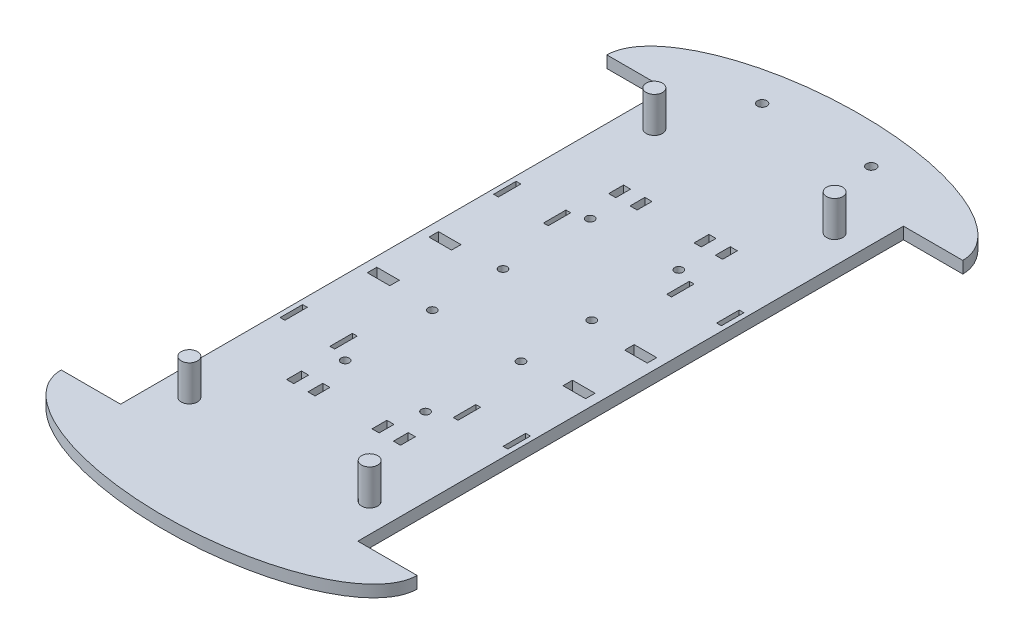
SolidWorks part; units mm, degrees
ref_plane "Front Plane" through (0, 0, 0) normal (0, 0, 1) x (1, 0, 0)
ref_plane "Top Plane" through (0, 0, 0) normal (0, 1, 0) x (1, 0, 0)
ref_plane "Right Plane" through (0, 0, 0) normal (1, 0, 0) x (0, 0, -1)
sketch "Sketch6" plane through (0, 0, 0) normal (0, 1, 0) x (1, 0, 0)
  line L0 (-75, -115) -> (75, -115)
  line L1 (-50, 115) -> (50, 115)
  line L2 (-50, 115) -> (-50, -115)
  line L3 (-50, -115) -> (50, -115)
  line L4 (50, 115) -> (50, -115)
  line L5 (-50, 115) -> (50, -115) construction
  line L6 (-50, -115) -> (50, 115) construction
  line L7 (-109.8149, 0) -> (148.3409, 0) construction
  line L8 (-75, 115) -> (75, 115)
  ellipse E0 centre (0, -115) end of major axis (75, -115) minor radius 31.707
  ellipse E1 centre (0, 115) end of major axis (75, 115) minor radius 31.707
  point P0 (0, 0)
  point P9 (0, -115)
  dimension "D1" = 230
  dimension "D2" = 100
extrude "Boss-Extrude10" add sketch "Sketch6" along normal blind 5 contours E1 L8 L1 | E1 L4 L1 L2 | L4 E1 L2 E0 | L4 E0 L2 L0 | L0 E0
sketch "Sketch8" plane through (0, 0, 0) normal (0, -1, 0) x (1, 0, 0)
sketch "Sketch9" plane through (0, 5, 0) normal (0, 1, 0) x (1, 0, 0)
  line L0 (-25, -45) -> (-25, -49.75) construction
  line L1 (-55, 0) -> (55, 0) construction
  line L2 (-46, -49.75) -> (-46, -40.25) construction
  line L3 (-48, -49.75) -> (-46, -49.75) construction
  line L4 (-48, -45) -> (-48, -40.25) construction
  line L5 (-48, 45) -> (-48, 49.75) construction
  line L6 (-48, 45) -> (-48, 40.25) construction
  line L7 (-48, 49.75) -> (-46, 49.75) construction
  line L8 (-46, 49.75) -> (-46, 40.25) construction
  line L9 (-48, -45) -> (-48, -49.75) construction
  line L10 (-48, 49.75) -> (-46, 49.75)
  line L11 (-48, 49.75) -> (-48, 40.25)
  line L12 (-48, 40.25) -> (-46, 40.25)
  line L13 (-46, 49.75) -> (-46, 40.25)
  line L14 (-46, -49.75) -> (-46, -40.25)
  line L15 (-48, -40.25) -> (-46, -40.25)
  line L16 (-48, -49.75) -> (-48, -40.25)
  line L17 (-48, -49.75) -> (-46, -49.75)
  line L18 (0, -55) -> (0, 55) construction
  line L19 (46, 49.75) -> (46, 40.25) construction
  line L20 (48, 49.75) -> (46, 49.75) construction
  line L21 (48, 45) -> (48, 40.25) construction
  line L22 (48, 45) -> (48, 49.75) construction
  line L23 (46, 49.75) -> (46, 40.25)
  line L24 (48, 40.25) -> (46, 40.25)
  line L25 (48, 49.75) -> (48, 40.25)
  line L26 (48, 49.75) -> (46, 49.75)
  line L27 (48, -45) -> (48, -49.75) construction
  line L28 (48, -45) -> (48, -40.25) construction
  line L29 (48, -49.75) -> (46, -49.75) construction
  line L30 (46, -49.75) -> (46, -40.25) construction
  line L31 (48, -49.75) -> (46, -49.75)
  line L32 (48, -49.75) -> (48, -40.25)
  line L33 (48, -40.25) -> (46, -40.25)
  line L34 (46, -49.75) -> (46, -40.25)
  line L35 (-27, 49.75) -> (-27, 40.25) construction
  line L37 (-25, 49.75) -> (-27, 49.75) construction
  line L38 (-25, 45) -> (-25, 40.25) construction
  line L39 (-25, 45) -> (-25, 49.75) construction
  line L40 (-27, 49.75) -> (-27, 40.25)
  line L41 (-25, 40.25) -> (-27, 40.25)
  line L42 (-25, 49.75) -> (-25, 40.25)
  line L43 (-25, 49.75) -> (-27, 49.75)
  line L44 (-25, -45) -> (-25, -40.25) construction
  line L45 (-25, -49.75) -> (-27, -49.75) construction
  line L46 (-27, -49.75) -> (-27, -40.25) construction
  line L47 (-25, -49.75) -> (-27, -49.75)
  line L48 (-25, -49.75) -> (-25, -40.25)
  line L49 (-25, -40.25) -> (-27, -40.25)
  line L50 (-27, -49.75) -> (-27, -40.25)
  line L51 (27, -49.75) -> (27, -40.25) construction
  line L52 (25, -49.75) -> (27, -49.75) construction
  line L53 (25, -45) -> (25, -40.25) construction
  line L54 (25, -45) -> (25, -49.75) construction
  line L55 (27, -49.75) -> (27, -40.25)
  line L56 (25, -40.25) -> (27, -40.25)
  line L57 (25, -49.75) -> (25, -40.25)
  line L58 (25, -49.75) -> (27, -49.75)
  line L59 (25, 45) -> (25, 49.75) construction
  line L60 (25, 45) -> (25, 40.25) construction
  line L61 (25, 49.75) -> (27, 49.75) construction
  line L62 (27, 49.75) -> (27, 40.25) construction
  line L63 (25, 49.75) -> (27, 49.75)
  line L64 (25, 49.75) -> (25, 40.25)
  line L65 (25, 40.25) -> (27, 40.25)
  line L66 (27, 49.75) -> (27, 40.25)
extrude "Cut-Extrude2" cut sketch "Sketch9" against normal through all
sketch "Sketch10" plane through (0, 5, 0) normal (0, 1, 0) x (1, 0, 0)
  line L0 (-15, -64.75) -> (-12, -64.75) construction
  line L2 (-15, -71) -> (-15, -64.75) construction
  line L3 (-24, -71) -> (-21, -71) construction
  line L4 (-24, -71) -> (-24, -64.75) construction
  line L5 (-21, -71) -> (-21, -64.75) construction
  line L6 (-21, -64.75) -> (-24, -64.75) construction
  line L7 (-12, -71) -> (-12, -64.75) construction
  line L8 (-24, -71) -> (-21, -71)
  line L9 (-24, -71) -> (-24, -64.75)
  line L10 (-24, -64.75) -> (-21, -64.75)
  line L11 (-21, -71) -> (-21, -64.75)
  line L12 (0, -55) -> (0, 55) construction
  line L13 (-12, -71) -> (-15, -71) construction
  line L14 (-15, -71) -> (-15, -64.75)
  line L15 (-12, -64.75) -> (-15, -64.75)
  line L16 (-12, -71) -> (-12, -64.75)
  line L17 (-12, -71) -> (-15, -71)
  line L18 (12, -71) -> (15, -71) construction
  line L19 (12, -71) -> (12, -64.75) construction
  line L20 (21, -64.75) -> (24, -64.75) construction
  line L21 (21, -71) -> (21, -64.75) construction
  line L22 (24, -71) -> (24, -64.75) construction
  line L23 (24, -71) -> (21, -71) construction
  line L24 (15, -71) -> (15, -64.75) construction
  line L25 (15, -64.75) -> (12, -64.75) construction
  line L26 (12, -71) -> (15, -71)
  line L27 (12, -71) -> (12, -64.75)
  line L28 (12, -64.75) -> (15, -64.75)
  line L29 (15, -71) -> (15, -64.75)
  line L30 (21, -71) -> (21, -64.75)
  line L31 (24, -64.75) -> (21, -64.75)
  line L32 (24, -71) -> (24, -64.75)
  line L33 (24, -71) -> (21, -71)
  line L34 (-55, 0) -> (55, 0) construction
  line L35 (15, 64.75) -> (12, 64.75) construction
  line L36 (15, 71) -> (15, 64.75) construction
  line L37 (24, 71) -> (21, 71) construction
  line L38 (24, 71) -> (24, 64.75) construction
  line L39 (21, 71) -> (21, 64.75) construction
  line L40 (21, 64.75) -> (24, 64.75) construction
  line L41 (12, 71) -> (12, 64.75) construction
  line L42 (12, 71) -> (15, 71) construction
  line L43 (-12, 71) -> (-15, 71) construction
  line L44 (-12, 71) -> (-12, 64.75) construction
  line L45 (-21, 64.75) -> (-24, 64.75) construction
  line L46 (-21, 71) -> (-21, 64.75) construction
  line L47 (-24, 71) -> (-24, 64.75) construction
  line L48 (-24, 71) -> (-21, 71) construction
  line L49 (-15, 71) -> (-15, 64.75) construction
  line L50 (-15, 64.75) -> (-12, 64.75) construction
  line L51 (24, 71) -> (21, 71)
  line L52 (24, 71) -> (24, 64.75)
  line L53 (24, 64.75) -> (21, 64.75)
  line L54 (21, 71) -> (21, 64.75)
  line L55 (15, 71) -> (15, 64.75)
  line L56 (12, 64.75) -> (15, 64.75)
  line L57 (12, 71) -> (12, 64.75)
  line L58 (12, 71) -> (15, 71)
  line L59 (-12, 71) -> (-15, 71)
  line L60 (-12, 71) -> (-12, 64.75)
  line L61 (-12, 64.75) -> (-15, 64.75)
  line L62 (-15, 71) -> (-15, 64.75)
  line L63 (-21, 71) -> (-21, 64.75)
  line L64 (-24, 64.75) -> (-21, 64.75)
  line L65 (-24, 71) -> (-24, 64.75)
  line L66 (-24, 71) -> (-21, 71)
extrude "Cut-Extrude3" cut sketch "Sketch10" against normal through all
sketch "Sketch11" plane through (0, 5, 0) normal (0, 1, 0) x (1, 0, 0)
  line L0 (0, -55) -> (0, 55) construction
  line L3 (36.5, -15) -> (36.5, -11) construction
  line L4 (36.5, -15) -> (46, -15) construction
  line L5 (-36.5, -15) -> (-46, -15) construction
  line L6 (-36.5, -15) -> (-36.5, -11) construction
  line L7 (46, -15) -> (46, -11)
  line L8 (-36.5, -15) -> (-46, -15)
  line L9 (-36.5, -15) -> (-36.5, -11)
  line L10 (-36.5, -11) -> (-46, -11)
  line L11 (-46, -15) -> (-46, -11)
  line L12 (36.5, -11) -> (46, -11)
  line L13 (36.5, -15) -> (36.5, -11)
  line L14 (36.5, -15) -> (46, -15)
  line L15 (-55, 0) -> (55, 0) construction
  line L16 (-36.5, 15) -> (-36.5, 11) construction
  line L17 (-36.5, 15) -> (-46, 15) construction
  line L18 (36.5, 15) -> (46, 15) construction
  line L19 (36.5, 15) -> (36.5, 11) construction
  line L20 (36.5, 15) -> (46, 15)
  line L21 (36.5, 15) -> (36.5, 11)
  line L22 (36.5, 11) -> (46, 11)
  line L23 (-46, 15) -> (-46, 11)
  line L24 (-36.5, 11) -> (-46, 11)
  line L25 (-36.5, 15) -> (-36.5, 11)
  line L26 (-36.5, 15) -> (-46, 15)
  line L27 (46, 15) -> (46, 11)
extrude "Cut-Extrude4" cut sketch "Sketch11" against normal through all
sketch "Sketch12" plane through (0, 5, 0) normal (0, 1, 0) x (1, 0, 0)
  line L0 (0, 83.293) -> (0, 116.707) construction
  line L1 (0, -55) -> (0, 55) construction
  line L2 (0, 116.707) -> (26.49, 116.707) construction
  line L3 (0, 116.707) -> (-26.49, 116.707) construction
  ellipse E0 centre (0, 115) end of major axis (75, 115) minor radius 31.707 (75, 115) -> (-75, 115) ccw construction
sketch "Sketch13" plane through (0, 5, 0) normal (0, 1, 0) x (1, 0, 0)
  line L0 (-50, 115) -> (50, 115) construction
  line L1 (0, -2.75) -> (0, 2.75) construction
  line L2 (-2.75, 0) -> (2.75, 0) construction
  line L4 (-38, 98) -> (-38, 115) construction
  circle A0 centre (-38, 98) radius 3.415
  circle A1 centre (38, 98) radius 3.415
  circle A2 centre (38, -98) radius 3.415
  circle A3 centre (-38, -98) radius 3.415
extrude "Boss-Extrude11" add sketch "Sketch13" along normal blind 15
sketch "Sketch14" plane through (0, 5, 0) normal (0, 1, 0) x (1, 0, 0)
  line L0 (-36.5, 15) -> (-36.5, 15.06) construction
  line L14 (16.99, -14.95) -> (18.74, -14.95) construction
  circle A0 centre (-18.7434, 14.9502) radius 1.75
  circle A1 centre (-18.7434, 51.6902) radius 1.75
  circle A3 centre (18.6366, 51.6902) radius 1.75
  circle A4 centre (18.6366, 14.9502) radius 1.75
  circle A11 centre (-18.64, -51.69) radius 1.75
  circle A12 centre (-18.64, -14.95) radius 1.75
  circle A13 centre (18.74, -14.95) radius 1.75
  circle A14 centre (16.99, -53.44) radius 1.75
extrude "Cut-Extrude5" cut sketch "Sketch14" against normal through all
sketch "Sketch15" plane through (0, 5, 0) normal (0, 1, 0) x (1, 0, 0)
  line L0 (-50, 115) -> (50, 115) construction
  line L1 (-24.5632, 130) -> (-24.5632, 115) construction
  line L2 (21.4168, 130) -> (21.4168, 115) construction
  circle A0 centre (-24.5632, 130) radius 2
  circle A1 centre (21.4168, 130) radius 2
  point P7 (-1.5732, 107.9298)
extrude "Cut-Extrude6" cut sketch "Sketch15" against normal through all
